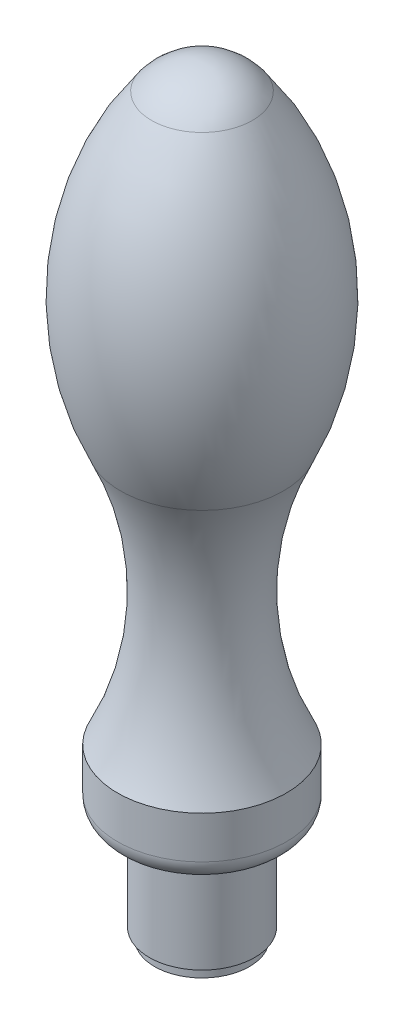
SolidWorks part; units mm, degrees
material "Teak"
ref_plane "Front Plane" through (0, 0, 0) normal (0, 0, 1) x (1, 0, 0)
ref_plane "Top Plane" through (0, 0, 0) normal (0, 1, 0) x (1, 0, 0)
ref_plane "Right Plane" through (0, 0, 0) normal (1, 0, 0) x (0, 0, -1)
sketch "Sketch1" plane through (0, 0, 0) normal (0, 0, 1) x (1, 0, 0)
  line L0 (0, 0) -> (-4.5, 0)
  line L1 (-4.5, 0) -> (-4.5, 1)
  line L2 (-4.5, 1) -> (-5, 1)
  line L3 (-5, 1) -> (-5, 10)
  line L4 (-5, 10) -> (-6, 10)
  line L5 (-8, 12) -> (-8, 16)
  line L6 (0, 0) -> (0, 134.9901) construction
  line L7 (0, 0) -> (0, 72)
  arc A0 (-8, 16) -> (-7.727, 40.6695) centre (-32.9983, 28.6129) ccw
  arc A1 (-7.727, 40.6695) -> (-4.7848, 69.6202) centre (17.5443, 52.7261) cw
  arc A2 (-4.7848, 69.6202) -> (0, 72) centre (0, 66) cw
  arc A3 (-6, 10) -> (-8, 12) centre (-6, 12) cw
  point P27 (-5, 28.3031)
  dimension "D7" = 28
  dimension "D8" = 28
  dimension "D9" = 6
  dimension "D12" = 2
  dimension "D1" = 4.5
  dimension "D2" = 1
  dimension "D3" = 5
  dimension "D4" = 8
  dimension "D5" = 10
  dimension "D6" = 6
  dimension "D10" = 72
  dimension "D11" = 5
revolve "Revolve1" add sketch "Sketch1" angle 360 about L6
